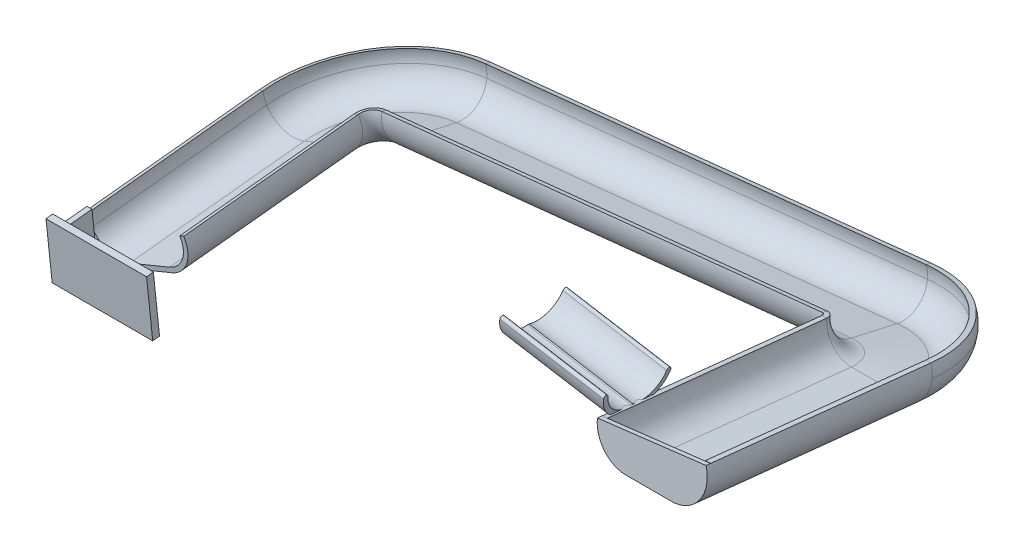
SolidWorks part; units mm, degrees
ref_plane "前视基准面" through (0, 0, 0) normal (0, 0, 1) x (1, 0, 0)
ref_plane "上视基准面" through (0, 0, 0) normal (0, 1, 0) x (1, 0, 0)
ref_plane "右视基准面" through (0, 0, 0) normal (1, 0, 0) x (0, 0, -1)
sketch3d "3D草图2"
  line L0 (5.9023, 0.6204, 0) -> (54.0977, 5.6859, 0)
  line L1 (0, 0, 0) -> (109.3127, 0, 0) construction
  line L2 (60, 6.3063, 0) -> (60, -19.8, 0) construction
  line L3 (60, 6.9266, 5.9023) -> (60, 9.4594, 30)
  line L4 (60, 6.3063, 0) -> (60, 6.3063, 23.8553) construction
  line L5 (60, 9.4594, 30) -> (60, 0.912, 30) construction
  line L6 (0, -0.6204, 5.9023) -> (0, -2.6276, 25)
  line L7 (0, 0, 0) -> (0, 0, 7.5975) construction
  line L8 (0, -2.6276, 25) -> (0, 1.8126, 25) construction
  arc A0 (0, -0.6204, 5.9023) -> (5.9023, 0.6204, 0) centre (5.9675, 0, 5.9675) ccw
  arc A1 (54.0977, 5.6859, 0) -> (60, 6.9266, 5.9023) centre (54.0325, 6.3063, 5.9675) ccw
  point P13 (0, 0, 0)
  point P15 (6.5913, -5.9348, 5.3437)
  point P18 (60, 6.3063, 0)
  point P20 (54.6563, 0.3715, 6.5913)
  point P21 (0, 0, 0)
  dimension "D10" = 6
  dimension "D1" = 6
  dimension "D2" = 60
  dimension "D3" = 60.3305
  dimension "D4" = 6
  dimension "D5" = 30
  dimension "D6" = 30.1652
  dimension "D7" = 6
  dimension "D8" = 25
  dimension "D9" = 25.1377
ref_plane "基准面1" through (60, 9.4594, 30) normal (0, 0.1045, 0.9945) x (1, 0, 0)
sketch "草图1" plane through (60, 9.4594, 30) normal (0, 0.1045, 0.9945) x (1, 0, 0)
  line L0 (-6, 3.25) -> (-5.5, 3.25)
  line L1 (-2.5, -0.25) -> (2.5, -0.25)
  line L3 (-2.5, 0.25) -> (2.5, 0.25)
  line L5 (-2.5, -0.25) -> (2.5, 0.25) construction
  line L6 (-2.5, 0.25) -> (2.5, -0.25) construction
  line L7 (0, -1.5175) -> (0, 2.5928) construction
  line L8 (0, 0) -> (0, -25.9633) construction
  line L11 (5.1988, 4.56) -> (5.7456, 4.56)
  arc A1 (-2.5, 0.25) -> (-5.5, 3.25) centre (-2.5, 3.25) cw
  arc A2 (-2.5, -0.25) -> (-6, 3.25) centre (-2.5, 3.25) cw
  arc A3 (2.5, -0.25) -> (6, 3.25) centre (2.5, 3.25) ccw
  arc A4 (2.5, 0.25) -> (5.5, 3.25) centre (2.5, 3.25) ccw
  arc A5 (5.5, 3.25) -> (5.1988, 4.56) centre (2.5, 3.25) ccw
  arc A6 (6, 3.25) -> (5.7456, 4.56) centre (2.5, 3.25) ccw
  point P0 (0, 0)
  dimension "D3" = 3
  dimension "D1" = 0.5
  dimension "D2" = 5
sweep "扫描1" add profiles "草图1" path "3D草图2"
sketch "草图2" plane through (0, -2.6276, 25) normal (0, -0.1045, 0.9945) x (1, 0, 0)
  line L1 (-6.6962, 2.6487) -> (-6.1498, 2.6487)
  line L2 (-6.6962, 2.6487) -> (-6.6962, -2.2697)
  line L3 (-6.6962, -2.2697) -> (-6.1498, -2.2697)
  line L4 (-6.1498, 2.6487) -> (-6.1498, -2.2697)
  line L5 (-6.6962, 2.6487) -> (-6.1498, -2.2697) construction
  line L6 (-6.6962, -2.2697) -> (-6.1498, 2.6487) construction
  point P0 (-6.423, 0.1895)
extrude "凸台-拉伸1" add sketch "草图2" along normal blind 3.6
sketch "草图3" plane through (-6.6962, 0, 0) normal (-1, 0, 0) x (0, 0, 1)
  line L0 (28.343, -5.2612) -> (29.0163, 1.145)
  line L1 (29.0163, 1.145) -> (29.7601, 1.0669)
  line L2 (29.7601, 1.0669) -> (29.0868, -5.3394)
  line L3 (29.0868, -5.3394) -> (28.343, -5.2612)
extrude "凸台-拉伸2" add sketch "草图3" against normal blind 11
sketch "草图5" plane through (0, 3.222, 30.6556) normal (0, 0.1045, 0.9945) x (1, 0, 0)
  line L2 (57.5, 6.0217) -> (62.5, 6.0217) construction
  line L3 (65.7456, 10.8318) -> (54, 9.5217)
  line L5 (57.5, 6.0217) -> (62.5, 6.0217)
  arc A3 (66, 9.5217) -> (65.7456, 10.8318) centre (62.5, 9.5217) ccw construction
  arc A4 (62.5, 6.0217) -> (66, 9.5217) centre (62.5, 9.5217) ccw construction
  arc A5 (54, 9.5217) -> (57.5, 6.0217) centre (57.5, 9.5217) ccw construction
  arc A9 (66, 9.5217) -> (65.7456, 10.8318) centre (62.5, 9.5217) ccw
  arc A10 (62.5, 6.0217) -> (66, 9.5217) centre (62.5, 9.5217) ccw
  arc A11 (54, 9.5217) -> (57.5, 6.0217) centre (57.5, 9.5217) ccw
  point P1 (0, 0)
extrude "凸台-拉伸4" add sketch "草图5" along normal blind 0.5
sketch3d "3D草图3"
  line L2 (53.9657, 12.4586, 26.5914) -> (42.9206, 14.3094, 26.5914)
  line L6 (0, 0, 0) -> (30.3842, 0, 0) construction
  point P0 (54, 12.3488, 26.3989)
ref_plane "基准面2" through (42.9206, 14.3094, 26.5914) normal (-0.9862, 0.1653, 0) x (0, 0, 1)
sketch "草图6" plane through (42.9206, 14.3094, 26.5914) normal (-0.9862, 0.1653, 0) x (0, 0, 1)
  line L2 (-0.6429, -0.6519) -> (0.7293, -0.5097)
  line L3 (0.1428, -0.014) -> (-0.0279, 0.0027)
  line L4 (-21.0289, -2.2625) -> (3.0688, 0.2355)
  line L5 (3.0688, 0.2355) -> (3.0688, 0.3181)
  line L6 (3.0688, 0.3181) -> (-21.0289, -2.1798)
  line L7 (-21.0289, -2.1798) -> (-21.0289, -2.2625)
  line L11 (-21.0289, -2.1798) -> (-21.0289, -2.2625)
  arc A0 (-0.0279, 0.0027) -> (-3.4861, 1.6063) centre (-0.9698, 2.5022) cw
  arc A1 (0.1428, -0.014) -> (3.0688, 2.5022) centre (0.4025, 2.6435) ccw
  arc A2 (-0.6429, -0.6519) -> (-3.9572, 1.4386) centre (-0.9698, 2.5022) cw
  arc A3 (0.7293, -0.5097) -> (3.5681, 2.4757) centre (0.4025, 2.6435) ccw
  arc A4 (-3.4861, 1.6063) -> (-3.9572, 1.4386) centre (-3.7217, 1.5224) ccw
  arc A5 (3.0688, 2.5022) -> (3.5681, 2.4757) centre (3.3185, 2.489) cw
  dimension "D1" = 0
extrude "凸台-拉伸5" add sketch "草图6" against normal blind 11.5 contours A5 A1 L3 A0 A4 A2 L2 A3
